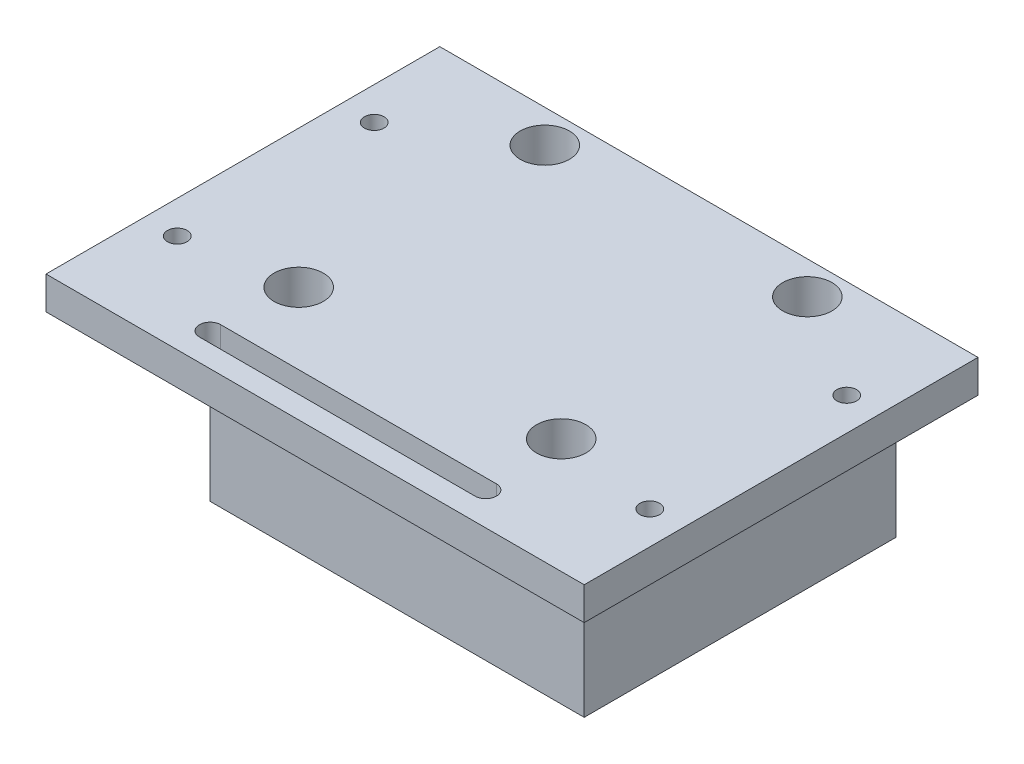
SolidWorks part; units mm, degrees
ref_plane "前视基准面" through (0, 0, 0) normal (0, 0, 1) x (1, 0, 0)
ref_plane "上视基准面" through (0, 0, 0) normal (0, 1, 0) x (1, 0, 0)
ref_plane "右视基准面" through (0, 0, 0) normal (1, 0, 0) x (0, 0, -1)
sketch "草图1" plane through (0, 0, 0) normal (0, 1, 0) x (1, 0, 0)
  line L1 (-57, 47.5) -> (57, 47.5)
  line L2 (-57, 47.5) -> (-57, -47.5)
  line L3 (-57, -47.5) -> (57, -47.5)
  line L4 (57, 47.5) -> (57, -47.5)
  line L5 (-57, 47.5) -> (57, -47.5) construction
  line L6 (-57, -47.5) -> (57, 47.5) construction
  point P0 (0, 0)
  dimension "D1" = 114
  dimension "D2" = 95
extrude "凸台-拉伸1" add sketch "草图1" along normal blind 60
sketch "草图7" plane through (0, 60, 0) normal (0, 1, 0) x (1, 0, 0)
  line L1 (-57, -47.5) -> (57, -47.5)
  line L2 (-57, -47.5) -> (-57, -72.5)
  line L3 (-57, -72.5) -> (57, -72.5)
  line L4 (57, -47.5) -> (57, -72.5)
  line L5 (-57, -72.5) -> (-82, -72.5)
  line L6 (-57, -72.5) -> (-57, 47.5)
  line L7 (-57, 47.5) -> (-82, 47.5)
  line L8 (-82, -72.5) -> (-82, 47.5)
  line L9 (57, -72.5) -> (82, -72.5)
  line L10 (57, -72.5) -> (57, 47.5)
  line L11 (57, 47.5) -> (82, 47.5)
  line L12 (82, -72.5) -> (82, 47.5)
  line M5 (57, -47.5) -> (57, 47.5)
  line M7 (-57, 47.5) -> (-57, -47.5)
  line M8 (-57, -47.5) -> (57, -47.5)
  dimension "D1" = 114
  dimension "D2" = 25
  dimension "D3" = 120
  dimension "D4" = 25
  dimension "D5" = 120
  dimension "D6" = 25
extrude "凸台-拉伸3" add sketch "草图7" against normal blind 10 contours L4 L2 L3 M8 | L8 L5 L2 L7 M7 | L9 L12 L11 L4 M5
sketch "草图14" plane through (0, 60, 0) normal (0, 1, 0) x (1, 0, 0)
  line L0 (-82, -72.5) -> (-82, -37.5)
  line L1 (-82, -72.5) -> (-82, 47.5) construction
  line L2 (-82, -37.5) -> (-40, -37.5)
  circle A0 centre (-40, -37.5) radius 7.5
  dimension "D3" = 15
  dimension "D1" = 35
  dimension "D2" = 42
extrude "切除-拉伸9" cut sketch "草图14" against normal blind 50 contours A0
sketch "草图15" plane through (0, 10, 0) normal (0, 1, 0) x (1, 0, 0)
  circle A0 centre (-40, -37.5) radius 3.3
  dimension "D1" = 6.6
extrude "切除-拉伸10" cut sketch "草图15" against normal blind 50
mirror "镜向1" about plane through (0, 0, 0) normal (1, 0, 0) of "切除-拉伸10", "切除-拉伸9"
mirror "镜向2" about plane through (0, 0, 0) normal (0, 0, 1) of "镜向1", "切除-拉伸9", "切除-拉伸10"
sketch "草图13" plane through (0, 50, 0) normal (0, -1, 0) x (1, 0, 0)
  line L0 (-57, 47.5) -> (-57, 72.5)
  line L1 (-82, 72.5) -> (82, 72.5) construction
  line L2 (-57, 72.5) -> (-42, 72.5)
  line L3 (-42, 72.5) -> (-42, 62.5)
  line L4 (57, 47.5) -> (57, 72.5)
  line L5 (57, 72.5) -> (42, 72.5)
  line L6 (42, 72.5) -> (42, 62.5)
  line L7 (-42, 62.5) -> (-42, 59.25)
  line L8 (-42, 59.25) -> (42, 59.25)
  line L9 (42, 65.75) -> (-42, 65.75)
  arc A0 (42, 59.25) -> (42, 65.75) centre (42, 62.5) ccw
  arc A1 (-42, 65.75) -> (-42, 59.25) centre (-42, 62.5) ccw
  dimension "D1" = 15
  dimension "D2" = 10
  dimension "D3" = 15
  dimension "D4" = 10
  dimension "D5" = 3.25
  dimension "D6" = 6.5
extrude "切除-拉伸8" cut sketch "草图13" against normal blind 10
sketch "草图16" plane through (0, 50, 0) normal (0, -1, 0) x (1, 0, 0)
  line L0 (-57, -47.5) -> (-72, -47.5)
  line L1 (-57, -47.5) -> (-82, -47.5) construction
  line L2 (-72, -47.5) -> (-72, -17.5)
  line L3 (-72, -17.5) -> (-72, 42.5)
  circle A0 centre (-72, -17.5) radius 3
  circle A1 centre (-72, 42.5) radius 3
  dimension "D4" = 6
  dimension "D5" = 6
  dimension "D1" = 15
  dimension "D2" = 30
  dimension "D3" = 60
extrude "切除-拉伸11" cut sketch "草图16" against normal blind 50 contours A1 | A0
mirror "镜向3" about plane through (0, 0, 0) normal (1, 0, 0) of "切除-拉伸11"
